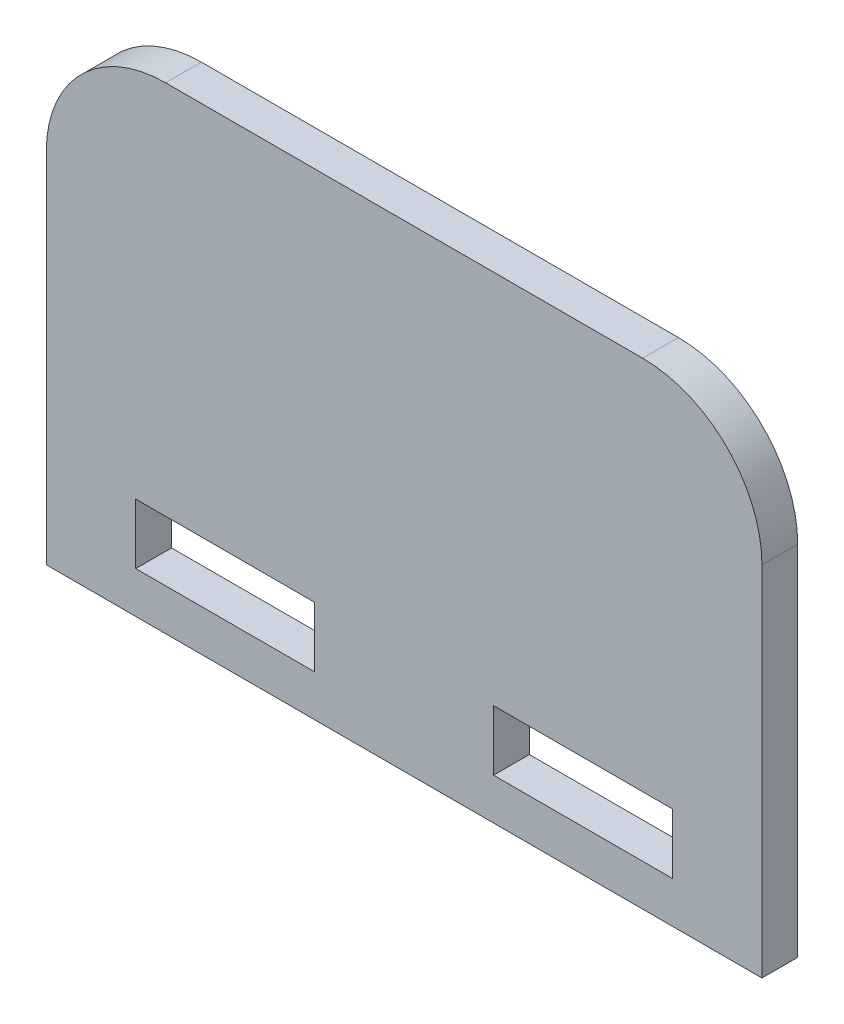
SolidWorks part; units mm, degrees
ref_plane "Plan de face" through (0, 0, 0) normal (0, 0, 1) x (1, 0, 0)
ref_plane "Plan de dessus" through (0, 0, 0) normal (0, 1, 0) x (1, 0, 0)
ref_plane "Plan de droite" through (0, 0, 0) normal (1, 0, 0) x (0, 0, -1)
sketch "Esquisse1" plane through (0, 0, 0) normal (0, 0, 1) x (1, 0, 0)
  line L0 (0, 14.9089) -> (0, -14.9089) construction
  line L1 (-20, 20) -> (20, 20)
  line L2 (-30, 10) -> (-30, -20)
  line L3 (-30, -20) -> (30, -20)
  line L4 (30, 10) -> (30, -20)
  line L5 (-30, 20) -> (30, -20) construction
  line L6 (-30, -20) -> (30, 20) construction
  line L7 (22.5, -16.525) -> (7.5, -16.525)
  line L8 (-22.5, -11.475) -> (-7.5, -11.475)
  line L9 (-22.5, -11.475) -> (-22.5, -16.525)
  line L10 (-22.5, -16.525) -> (-7.5, -16.525)
  line L11 (-7.5, -11.475) -> (-7.5, -16.525)
  line L12 (-22.5, -11.475) -> (-7.5, -16.525) construction
  line L13 (-22.5, -16.525) -> (-7.5, -11.475) construction
  line L14 (7.5, -11.475) -> (7.5, -16.525)
  line L15 (22.5, -11.475) -> (7.5, -11.475)
  line L16 (22.5, -11.475) -> (22.5, -16.525)
  arc A0 (20, 20) -> (30, 10) centre (20, 10) cw
  arc A1 (-20, 20) -> (-30, 10) centre (-20, 10) ccw
  point P0 (0, 0)
  point P9 (0, 0)
  point P10 (-15, -14)
  dimension "D7" = 10
  dimension "D1" = 60
  dimension "D2" = 40
  dimension "D3" = 6
  dimension "D4" = 5.05
  dimension "D5" = 15
  dimension "D6" = 15
extrude "Boss.-Extru.1" add sketch "Esquisse1" along normal blind 3
